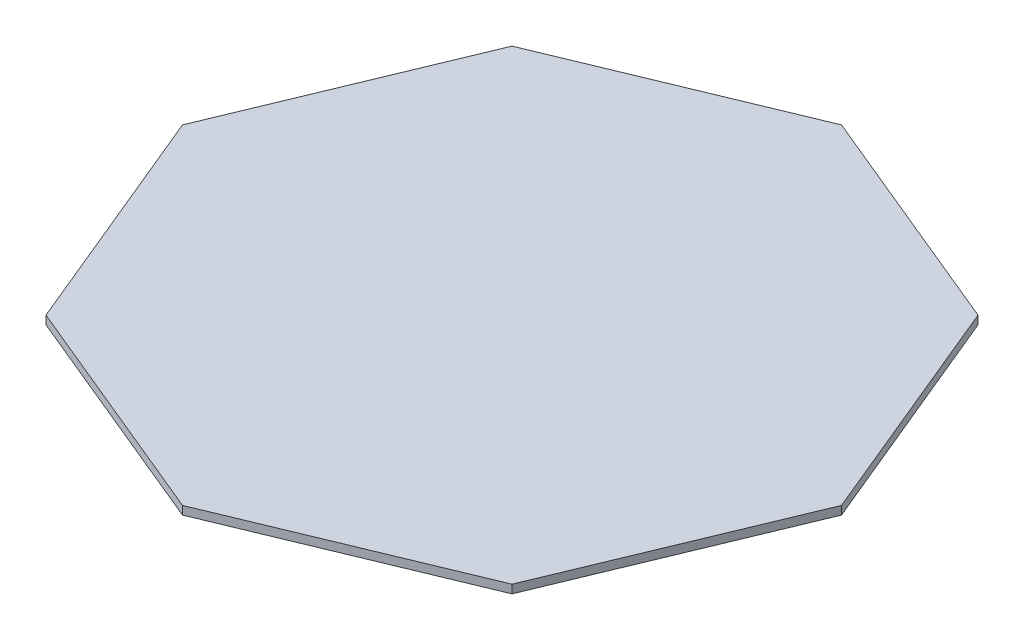
SolidWorks part; units mm, degrees
ref_plane "Front Plane" through (0, 0, 0) normal (0, 0, 1) x (1, 0, 0)
ref_plane "Top Plane" through (0, 0, 0) normal (0, 1, 0) x (1, 0, 0)
ref_plane "Right Plane" through (0, 0, 0) normal (1, 0, 0) x (0, 0, -1)
sketch "Sketch1" plane through (0, 0, 0) normal (0, 1, 0) x (1, 0, 0)
  line L1 (78.4734, 0) -> (55.4891, 55.4891)
  line L2 (55.4891, 55.4891) -> (0, 78.4734)
  line L3 (0, 78.4734) -> (-55.4891, 55.4891)
  line L4 (-55.4891, 55.4891) -> (-78.4734, 0)
  line L5 (-78.4734, 0) -> (-55.4891, -55.4891)
  line L6 (-55.4891, -55.4891) -> (0, -78.4734)
  line L7 (0, -78.4734) -> (55.4891, -55.4891)
  line L8 (55.4891, -55.4891) -> (78.4734, 0)
  circle A0 centre (0, 0) radius 72.5 construction
  dimension "D1" = 145
extrude "Boss-Extrude1" add sketch "Sketch1" along normal blind 2
